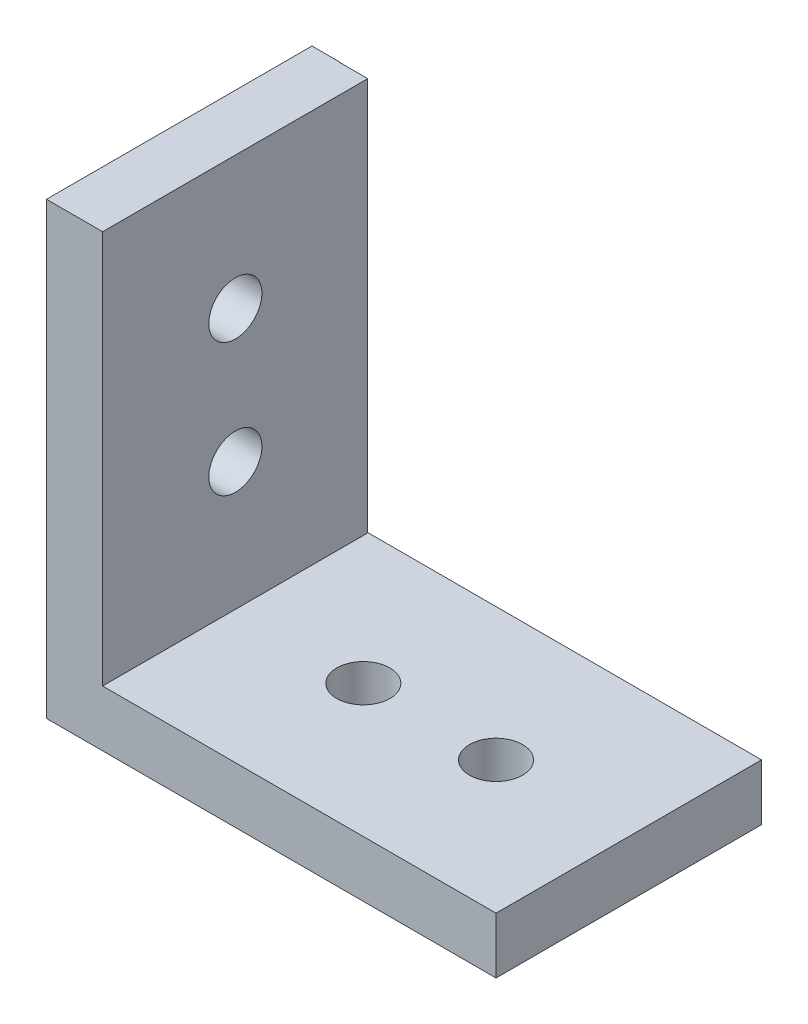
SolidWorks part; units mm, degrees
ref_plane "Front Plane" through (0, 0, 0) normal (0, 0, 1) x (1, 0, 0)
ref_plane "Top Plane" through (0, 0, 0) normal (0, 1, 0) x (1, 0, 0)
ref_plane "Right Plane" through (0, 0, 0) normal (1, 0, 0) x (0, 0, -1)
sketch "Sketch1" plane through (0, 0, 0) normal (1, 0, 0) x (0, 0, -1)
  line L1 (0, 0) -> (15, 0)
  line L2 (0, 0) -> (0, 25.4)
  line L3 (0, 25.4) -> (15, 25.4)
  line L4 (15, 0) -> (15, 25.4)
  dimension "D1" = 25.4
  dimension "D2" = 15
extrude "Boss-Extrude1" add sketch "Sketch1" along normal blind 3.175
sketch "Sketch2" plane through (3.175, 0, 0) normal (1, 0, 0) x (0, 0, -1)
  line L0 (15, 0) -> (15, 25.4) construction
  line L1 (0, 0) -> (15, 0)
  line L2 (0, 0) -> (0, 3.175)
  line L3 (0, 3.175) -> (15, 3.175)
  line L4 (15, 0) -> (15, 3.175)
  dimension "D1" = 3.175
extrude "Boss-Extrude2" add sketch "Sketch2" along normal blind 22.225
sketch "Sketch3" plane through (0, 0, 0) normal (0, -1, 0) x (1, 0, 0)
  circle A2 centre (10.4, -7.5) radius 1.5
  circle A3 centre (17.9, -7.5) radius 1.5
sketch "Sketch4" plane through (3.175, 0, 0) normal (1, 0, 0) x (0, 0, -1)
  line L0 (7.5, 25.4) -> (7.5, 10.4)
  line L1 (15, 25.4) -> (0, 25.4) construction
  circle A0 centre (7.5, 17.9) radius 1.5
  circle A1 centre (7.5, 10.4) radius 1.5
  dimension "D1" = 15
extrude "Cut-Extrude3" cut sketch "Sketch4" against normal through all contours A0 | A1
extrude "Cut-Extrude4" cut sketch "Sketch3" against normal through all
sketch "Sketch5" plane through (0, 3.175, 0) normal (0, 1, 0) x (1, 0, 0)
  line L1 (3.175, 0) -> (25.4, 0)
  line L2 (3.175, 0) -> (3.175, 15)
  line L3 (3.175, 15) -> (25.4, 15)
  line L4 (25.4, 0) -> (25.4, 15)
extrude "Cut-Extrude5" cut sketch "Sketch5" against normal up to vertex (1.5875 mm away)
sketch "Sketch6" plane through (3.175, 0, 0) normal (1, 0, 0) x (0, 0, -1)
  line L1 (0, 1.5875) -> (15, 1.5875)
  line L2 (0, 1.5875) -> (0, 25.4)
  line L3 (0, 25.4) -> (15, 25.4)
  line L4 (15, 1.5875) -> (15, 25.4)
extrude "Cut-Extrude6" cut sketch "Sketch6" against normal up to vertex
sketch "Sketch7" plane through (0, 1.5875, 0) normal (0, 1, 0) x (1, 0, 0)
  line L1 (1.5875, 15) -> (25.4, 15)
  line L2 (1.5875, 15) -> (1.5875, 0)
  line L3 (1.5875, 0) -> (25.4, 0)
  line L4 (25.4, 15) -> (25.4, 0)
  circle A0 centre (10.4, 7.5) radius 1.5
  circle A1 centre (17.9, 7.5) radius 1.5
extrude "Boss-Extrude5" add sketch "Sketch7" along normal blind 1.585
sketch "Sketch8" plane through (1.5875, 0, 0) normal (1, 0, 0) x (0, 0, -1)
  line L0 (15, 3.1725) -> (0, 3.1725) construction
  line L1 (0, 25.4) -> (14.9789, 25.4)
  line L2 (0, 25.4) -> (0, 3.1725)
  line L3 (0, 3.1725) -> (14.9789, 3.1725)
  line L4 (14.9789, 25.4) -> (14.9789, 3.1725)
  circle A0 centre (7.5, 17.9) radius 1.5
  circle A1 centre (7.5, 10.4) radius 1.5
extrude "Boss-Extrude6" add sketch "Sketch8" along normal blind 1.585
